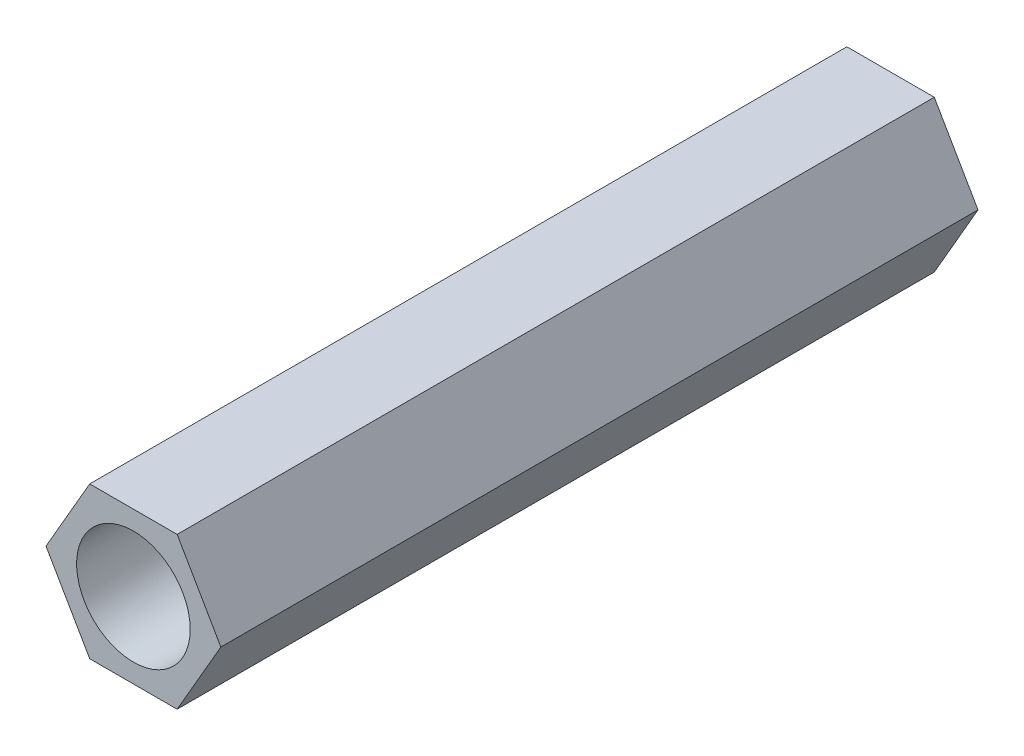
SolidWorks part; units mm, degrees
ref_plane "前视基准面" through (0, 0, 0) normal (0, 0, 1) x (1, 0, 0)
ref_plane "上视基准面" through (0, 0, 0) normal (0, 1, 0) x (1, 0, 0)
ref_plane "右视基准面" through (0, 0, 0) normal (1, 0, 0) x (0, 0, -1)
other "Configuration Table"
sketch "草图1" plane through (0, 0, 0) normal (0, 0, 1) x (1, 0, 0)
  line L1 (2.3094, 0) -> (1.1547, 2)
  line L2 (1.1547, 2) -> (-1.1547, 2)
  line L3 (-1.1547, 2) -> (-2.3094, 0)
  line L4 (-2.3094, 0) -> (-1.1547, -2)
  line L5 (-1.1547, -2) -> (1.1547, -2)
  line L6 (1.1547, -2) -> (2.3094, 0)
  circle A0 centre (0, 0) radius 2 construction
  circle A1 centre (0, 0) radius 1.5
  dimension "D1" = 2
extrude "凸台-拉伸1" add sketch "草图1" along normal blind 20
